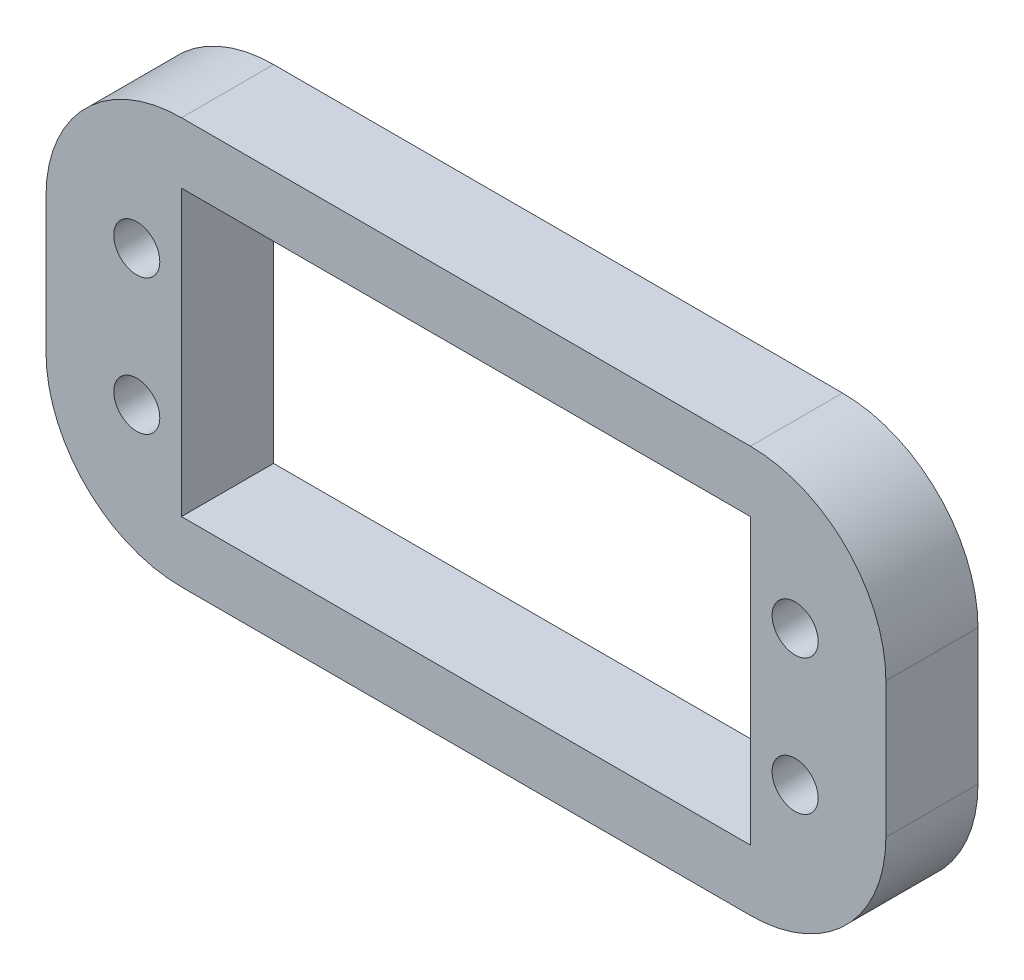
SolidWorks part; units mm, degrees
ref_plane "前视基准面" through (0, 0, 0) normal (0, 0, 1) x (1, 0, 0)
ref_plane "上视基准面" through (0, 0, 0) normal (0, 1, 0) x (1, 0, 0)
ref_plane "右视基准面" through (0, 0, 0) normal (1, 0, 0) x (0, 0, -1)
sketch "草图1" plane through (0, 0, 0) normal (0, 0, 1) x (1, 0, 0)
  line L0 (0, 15) -> (62, 15) construction
  line L1 (0, 0) -> (62, 0)
  line L2 (0, 0) -> (0, 30)
  line L3 (0, 30) -> (62, 30)
  line L4 (62, 0) -> (62, 30)
  line L5 (31, 30) -> (31, 0) construction
  line L6 (10, 25.5) -> (52, 25.5)
  line L7 (10, 25.5) -> (10, 4.5)
  line L8 (10, 4.5) -> (52, 4.5)
  line L9 (52, 25.5) -> (52, 4.5)
  line L10 (6.7, 15) -> (6.7, 30) construction
  circle A0 centre (6.7, 20) radius 1.7
  circle A1 centre (6.7, 10) radius 1.7
  circle A2 centre (55.3, 10) radius 1.7
  circle A3 centre (55.3, 20) radius 1.7
  dimension "D6" = 3.4
  dimension "D7" = 3.4
  dimension "D1" = 30
  dimension "D2" = 21
  dimension "D3" = 42
  dimension "D4" = 10
  dimension "D5" = 24.3
  dimension "D8" = 10
extrude "凸台-拉伸1" add sketch "草图1" along normal blind 6.8
fillet "圆角1" radius 10 4 edges at (0, 30, 3.4) (62, 30, 3.4) (62, 0, 3.4) (0, 0, 3.4)
